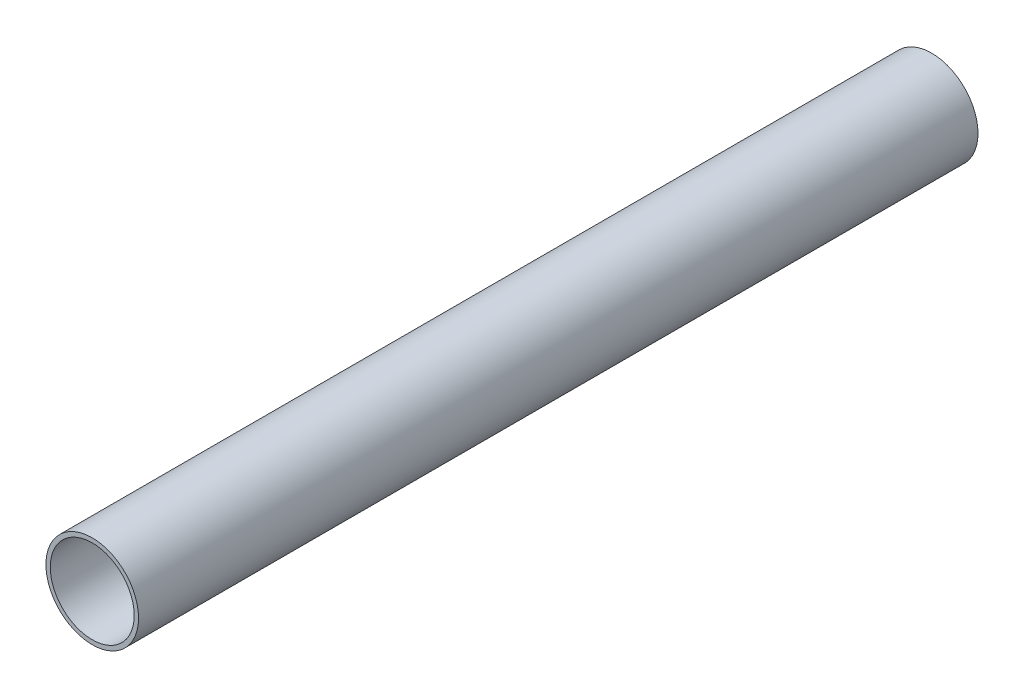
SolidWorks part; units mm, degrees
material "5052 Alloy"
ref_plane "Front Plane" through (0, 0, 0) normal (0, 0, 1) x (1, 0, 0)
ref_plane "Top Plane" through (0, 0, 0) normal (0, 1, 0) x (1, 0, 0)
ref_plane "Right Plane" through (0, 0, 0) normal (1, 0, 0) x (0, 0, -1)
sketch "Sketch1" plane through (0, 0, 0) normal (1, 0, 0) x (0, 0, -1)
  line L0 (-72.5, 0) -> (72.5, 0) construction
  line L8 (72.5, 8) -> (-72.5, 8)
  line L9 (-72.5, 8) -> (-72.5, 7.25)
  line L10 (-72.5, 7.25) -> (72.5, 7.25)
  line L11 (72.5, 7.25) -> (72.5, 8)
  dimension "D1" = 14.5
  dimension "D2" = 16
  dimension "D3" = 145
revolve "Revolve1" add sketch "Sketch1" angle 360 about L0
